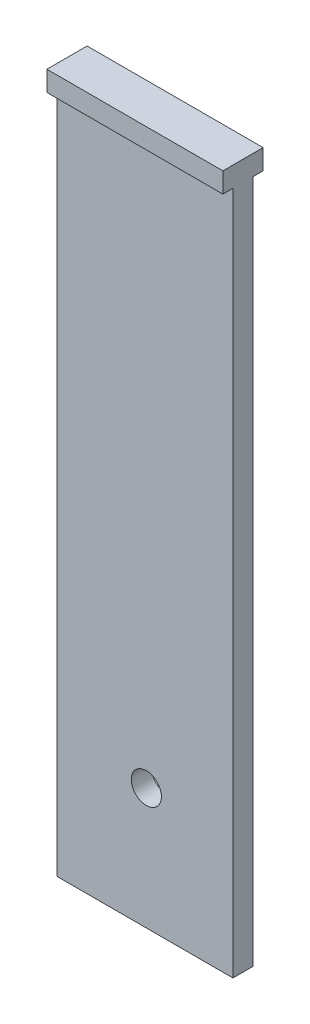
SolidWorks part; units mm, degrees
ref_plane "Front Plane" through (0, 0, 0) normal (0, 0, 1) x (1, 0, 0)
ref_plane "Top Plane" through (0, 0, 0) normal (0, 1, 0) x (1, 0, 0)
ref_plane "Right Plane" through (0, 0, 0) normal (1, 0, 0) x (0, 0, -1)
sketch "Sketch1" plane through (0, 0, 0) normal (0, 0, 1) x (1, 0, 0)
  line L1 (17.5, 70) -> (-17.5, 70)
  line L2 (17.5, 70) -> (17.5, -70)
  line L3 (17.5, -70) -> (-17.5, -70)
  line L4 (-17.5, 70) -> (-17.5, -70)
  line L5 (17.5, 70) -> (-17.5, -70) construction
  line L6 (17.5, -70) -> (-17.5, 70) construction
  arc A1 (-1.8441, -48.0247) -> (-0.8196, -43.111) centre (0.2772, -45.9033) ccw construction
  circle A2 centre (0.2772, -45.9033) radius 3
  point P0 (0, 0)
  point P7 (0, 0)
  dimension "D3" = 6
  dimension "D1" = 35
  dimension "D2" = 140
extrude "Boss-Extrude1" add sketch "Sketch1" along normal blind 4
sketch "Sketch2" plane through (0, 70, 0) normal (0, 1, 0) x (1, 0, 0)
  line L0 (17.5, 0) -> (-17.5, 0) construction
  line L1 (-17.5, 2) -> (17.5, 2)
  line L2 (-17.5, 2) -> (-17.5, -6)
  line L3 (-17.5, -6) -> (17.5, -6)
  line L4 (17.5, 2) -> (17.5, -6)
  line L5 (-17.5, 2) -> (17.5, -6) construction
  line L6 (-17.5, -6) -> (17.5, 2) construction
  line L7 (17.5, -4) -> (-17.5, -4) construction
  point P0 (0, -2)
  dimension "D1" = 2
  dimension "D2" = 2
extrude "Boss-Extrude2" add sketch "Sketch2" against normal blind 4
